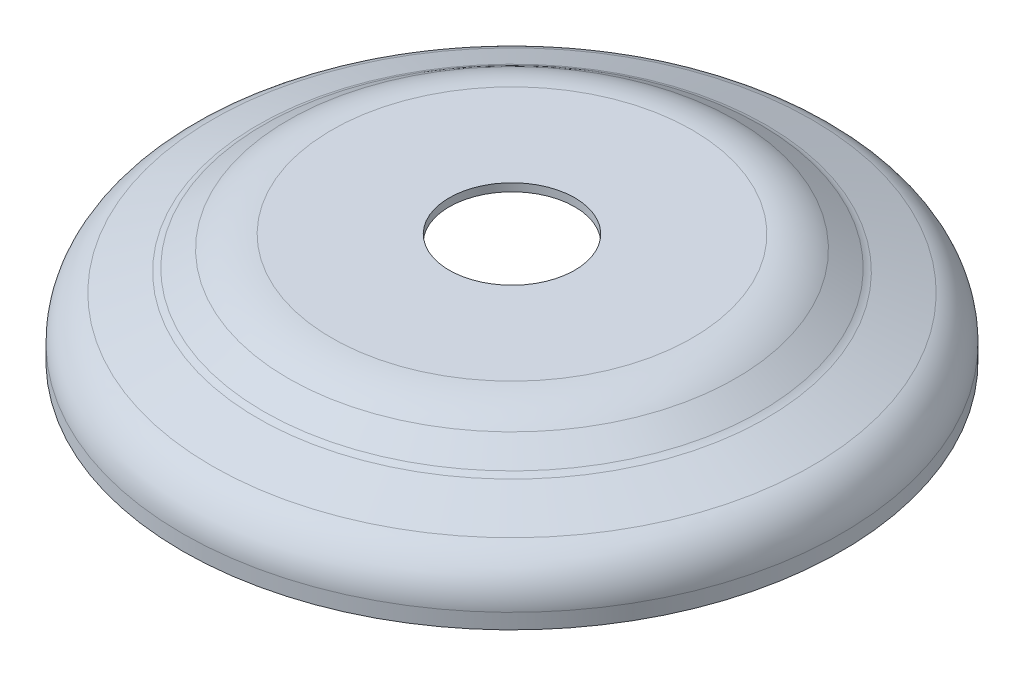
SolidWorks part; units mm, degrees
material "Vanadium"
ref_plane "Front Plane" through (0, 0, 0) normal (0, 0, 1) x (1, 0, 0)
ref_plane "Top Plane" through (0, 0, 0) normal (0, 1, 0) x (1, 0, 0)
ref_plane "Right Plane" through (0, 0, 0) normal (1, 0, 0) x (0, 0, -1)
sketch "Sketch2" plane through (0, 0, 0) normal (1, 0, 0) x (0, 0, -1)
  line L0 (0, 0) -> (0, 7) construction
  line L1 (4, 7) -> (11.4861, 7)
  line L2 (21, 0.9689) -> (21, 0)
  line L3 (21, 0) -> (20.5, 0)
  line L4 (4, 6.5) -> (11.4861, 6.5)
  line L5 (0, 0) -> (0, 7) construction
  line L6 (4, 7) -> (4, 6.5)
  line L7 (13.9823, 5.7442) -> (15.5494, 4.6995)
  line L8 (16.0077, 4.4584) -> (18.9285, 3.2901)
  line L9 (20.5, 0.9689) -> (20.5, 0)
  line L12 (20.5, 0.9689) -> (20.5, 0.5) construction
  line L13 (4.5, 6.5) -> (11.4861, 6.5) construction
  line L14 (4, 7) -> (4, 0) construction
  line L15 (14.2596, 6.1603) -> (15.8267, 5.1155)
  line L16 (21, 0) -> (4, 0) construction
  line L17 (16.1933, 4.9227) -> (19.1142, 3.7543)
  line L18 (4.5, 6.5) -> (4.5, 0.5) construction
  line L19 (20.5, 0.5) -> (4.5, 0.5) construction
  arc A0 (11.4861, 7) -> (14.2596, 6.1603) centre (11.4861, 2) cw
  arc A1 (16.1933, 4.9227) -> (15.8267, 5.1155) centre (16.9361, 6.7796) cw
  arc A2 (21, 0.9689) -> (19.1142, 3.7543) centre (18, 0.9689) ccw
  arc A3 (11.4861, 6.5) -> (13.9823, 5.7442) centre (11.4861, 2) cw
  arc A4 (16.0077, 4.4584) -> (15.5494, 4.6995) centre (16.9361, 6.7796) cw
  arc A5 (20.5, 0.9689) -> (18.9285, 3.2901) centre (18, 0.9689) ccw
  dimension "D2" = 5
  dimension "D3" = 2
  dimension "D4" = 3
  dimension "D1" = 7
  dimension "D5" = 0.5
revolve "Revolve1" add sketch "Sketch2" angle 360 about L0
